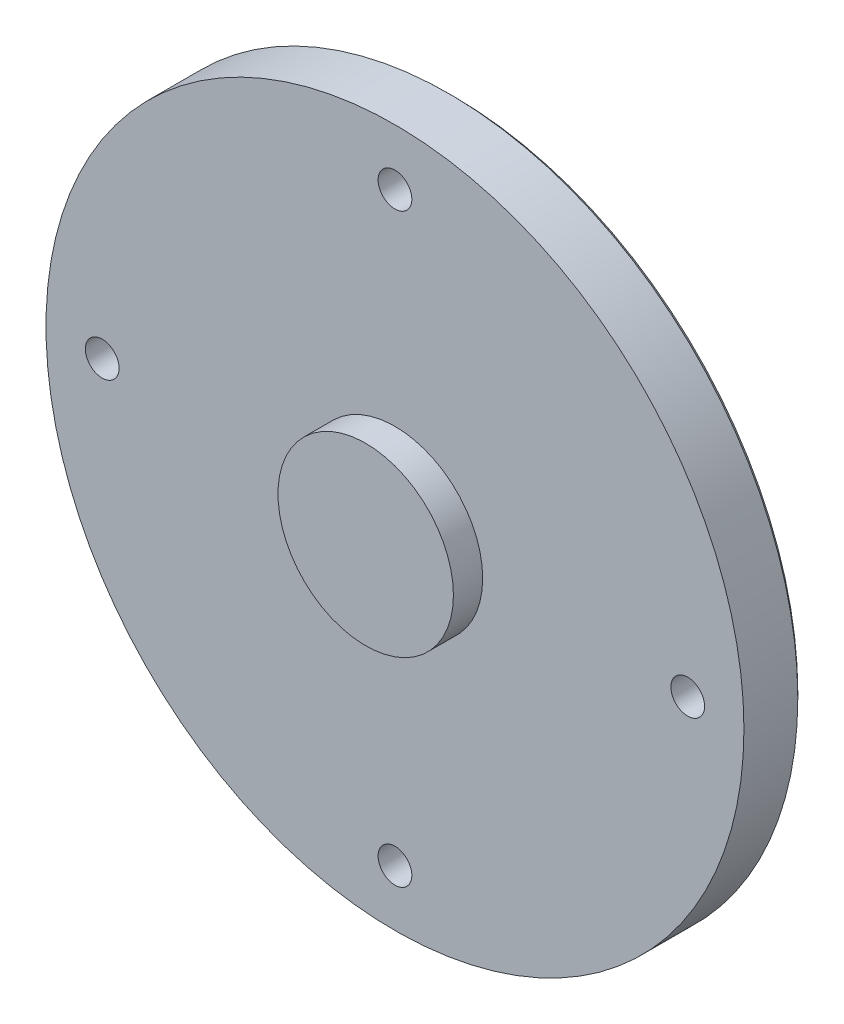
SolidWorks part; units mm, degrees
ref_plane "Front Plane" through (0, 0, 0) normal (0, 0, 1) x (1, 0, 0)
ref_plane "Top Plane" through (0, 0, 0) normal (0, 1, 0) x (1, 0, 0)
ref_plane "Right Plane" through (0, 0, 0) normal (1, 0, 0) x (0, 0, -1)
sketch "Sketch1" plane through (0, 0, 0) normal (1, 0, 0) x (0, 0, -1)
  line L1 (-22.225, 0) -> (-22.225, 9.5123)
  line L2 (-22.225, 9.5123) -> (-19.05, 9.5123)
  line L3 (-19.05, 9.5123) -> (-19.05, 37.846)
  line L4 (-19.05, 37.846) -> (-12.7, 37.846)
  line L5 (-12.7, 37.846) -> (-12.7, 12.6492)
  line L6 (-12.7, 12.6492) -> (0, 12.6492)
  line L7 (0, 12.6492) -> (0, 0)
  line L9 (-22.225, 0) -> (0, 0)
  point P0 (-15.875, 37.846)
  dimension "D1" = 9.5123
  dimension "D2" = 3.175
  dimension "D3" = 37.846
  dimension "D4" = 12.7
  dimension "D5" = 12.6492
  dimension "D6" = 6.35
revolve "Revolve1" add sketch "Sketch1" angle 360 about L9
sketch "Sketch2" plane through (0, 0, 12.7) normal (0, 0, -1) x (-1, 0, 0)
  line L0 (-37.846, 0) -> (37.846, 0) construction
  line L1 (0, 37.846) -> (0, -37.846) construction
  circle A0 centre (0, 0) radius 37.846 construction
  circle A1 centre (0, 0) radius 31.75 construction
  point P11 (0, 31.75)
  point P13 (31.75, 0)
  point P15 (0, -31.75)
  point P17 (-31.75, 0)
  point P20 (0, 0)
  point P21 (34.2221, 0)
  point P22 (0, 28.2891)
  point P23 (0, 0)
  point P24 (0, -31.75)
  point P25 (-31.75, 0)
  dimension "D1" = 63.5
hole_wizard "CBORE for #6 Socket Head Cap Screw1" positions "Sketch2" profile "Sketch3" counterbore size "#6" standard "ANSI Inch" end condition through all
sketch "Sketch3" plane through (31.75, 0, 12.7) normal (1, 0, 0) x (0, 1, 0)
  line L0 (0, 0) -> (0, 9.525)
  line L1 (0, 9.525) -> (1.8288, 9.525)
  line L3 (1.8288, 9.525) -> (1.8288, 3.5052)
  line L4 (1.8288, 3.5052) -> (3.5725, 3.5052)
  line L5 (3.5725, 3.5052) -> (3.5725, 0)
  line L7 (3.5725, 0) -> (0, 0)
  line L11 (0, -6.35) -> (0, 107.95) construction
  dimension "Thru Hole Dia." = 3.6576
  dimension "Thru Hole Depth" = 9.525
  dimension "C'Bore Dia." = 7.145
  dimension "C'Bore Depth" = 3.5052
chamfer "Chamfer1" distance 0.508 angle 45 2 edges at (37.846, 0, 12.7) (12.6492, 0, 0)
